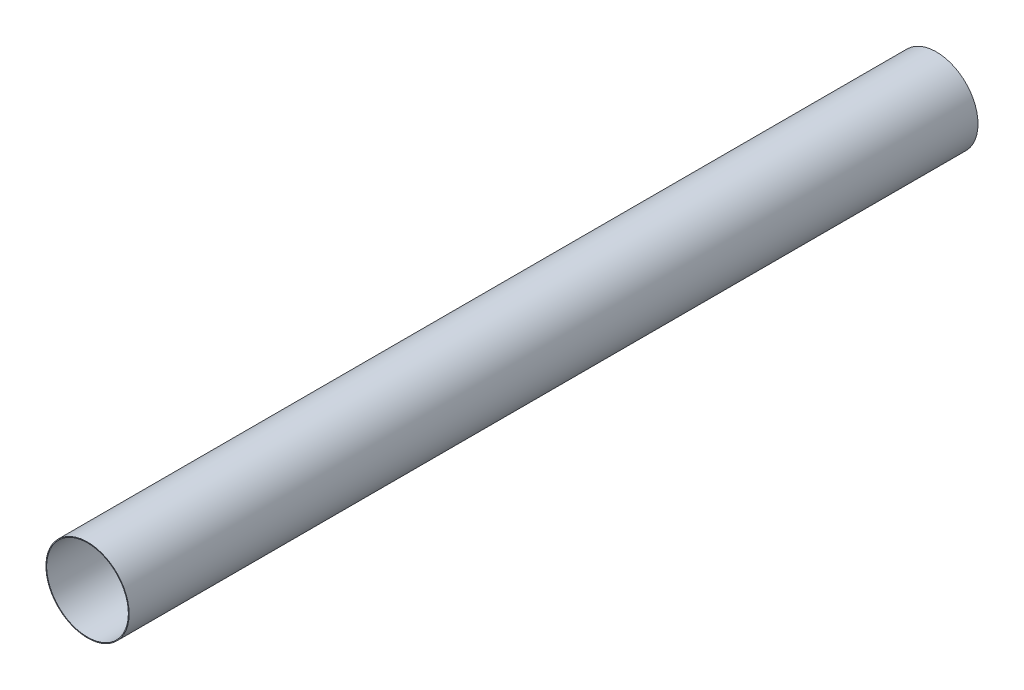
SolidWorks part; units mm, degrees
ref_plane "Front Plane" through (0, 0, 0) normal (0, 0, 1) x (1, 0, 0)
ref_plane "Top Plane" through (0, 0, 0) normal (0, 1, 0) x (1, 0, 0)
ref_plane "Right Plane" through (0, 0, 0) normal (1, 0, 0) x (0, 0, -1)
sketch "Sketch1" plane through (0, 0, 0) normal (0, 0, 1) x (1, 0, 0)
  circle A0 centre (0, 0) radius 55
  circle A1 centre (0, 0) radius 56
extrude "Boss-Extrude1" add sketch "Sketch1" along normal blind 1143
